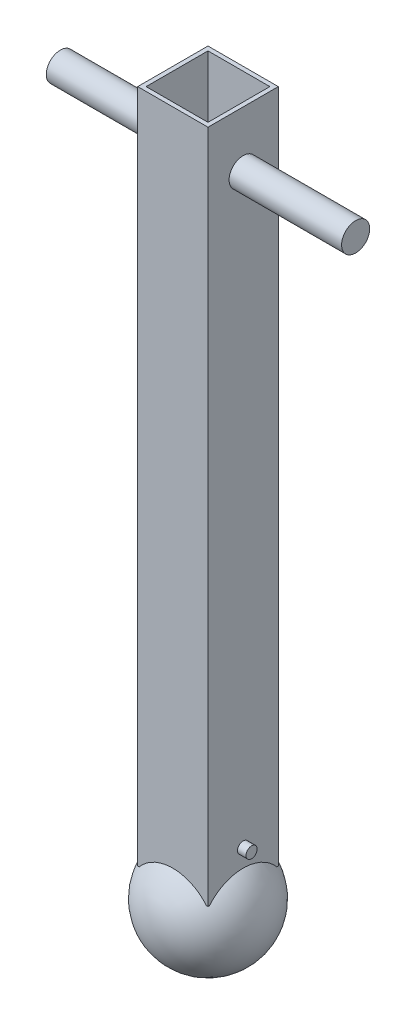
SolidWorks part; units mm, degrees
ref_plane "Front Plane" through (0, 0, 0) normal (0, 0, 1) x (1, 0, 0)
ref_plane "Top Plane" through (0, 0, 0) normal (0, 1, 0) x (1, 0, 0)
ref_plane "Right Plane" through (0, 0, 0) normal (1, 0, 0) x (0, 0, -1)
sketch "Sketch1" plane through (0, 0, 0) normal (0, 1, 0) x (1, 0, 0)
  line L0 (0, 56.0843) -> (0, -54.0393) construction
  line L1 (-85.0637, 0) -> (105.2276, 0) construction
  line L3 (-12.5, 12.5) -> (12.5, 12.5)
  line L4 (-12.5, 12.5) -> (-12.5, -12.5)
  line L5 (-12.5, -12.5) -> (12.5, -12.5)
  line L6 (12.5, 12.5) -> (12.5, -12.5)
  line L7 (-12.5, 12.5) -> (12.5, -12.5) construction
  line L8 (-12.5, -12.5) -> (12.5, 12.5) construction
  point P5 (0, 0)
  dimension "D1" = 25
  dimension "D2" = 25
extrude "Boss-Extrude1" add sketch "Sketch1" along normal blind 240
sketch "Sketch3" plane through (0, 0, 0) normal (0, -1, 0) x (1, 0, 0)
  line L0 (0, 13.6526) -> (0, -14.5281) construction
  line L1 (-18.6047, 0) -> (18.7142, 0) construction
  line L4 (-11, 11) -> (11, 11)
  line L5 (-11, 11) -> (-11, -11)
  line L6 (-11, -11) -> (11, -11)
  line L7 (11, 11) -> (11, -11)
  line L8 (-11, 11) -> (11, -11) construction
  line L9 (-11, -11) -> (11, 11) construction
  point P5 (0, 0)
  dimension "D1" = 22
  dimension "D2" = 22
extrude "Cut-Extrude1" cut sketch "Sketch3" against normal blind 300
ref_plane "Plane1" through (0, -10, 0) normal (0, -1, 0) x (-1, 0, 0)
sketch "Sketch4" plane through (0, -10, 0) normal (0, -1, 0) x (-1, 0, 0)
  line L0 (0, 13.2121) -> (0, -13.9344) construction
  line L1 (0, 20) -> (0, -20)
  arc A0 (0, 20) -> (0, -20) centre (0, 0) ccw
  dimension "D2" = 20
  dimension "D1" = 40
revolve "Revolve1" add sketch "Sketch4" angle 360 about L0
sketch "Sketch6" plane through (12.5, 0, 0) normal (1, 0, 0) x (0, 0, -1)
  line L0 (0, 22.0983) -> (0, -32.6766) construction
  line L1 (41.5847, -10) -> (-39.8607, -10) construction
  line L2 (-0.2807, -10) -> (0.2807, -10) construction
  circle A0 centre (0, 12) radius 2
  dimension "D2" = 4
  dimension "D1" = 22
extrude "Cut-Extrude3" cut sketch "Sketch6" against normal blind 25
sketch "Sketch9" plane through (-12.5, 0, 0) normal (-1, 0, 0) x (0, 0, 1)
  circle A0 centre (0, 12) radius 1.99
extrude "Boss-Extrude8" add sketch "Sketch9" against normal blind 28 separate body
sketch "Sketch10" plane through (-12.5, 0, 0) normal (-1, 0, 0) x (0, 0, 1)
  circle A0 centre (0, 12) radius 1.99
extrude "Boss-Extrude9" add sketch "Sketch10" along normal blind 3
sketch "Sketch13" plane through (0, 0, 0) normal (1, 0, 0) x (0, 0, -1)
  line L0 (-12.5, 240) -> (12.5, 240) construction
  circle A1 centre (0, 220) radius 5
  dimension "D1" = 20
extrude "Boss-Extrude11" add sketch "Sketch13" along normal blind 52.5 and the other way blind 52.5
